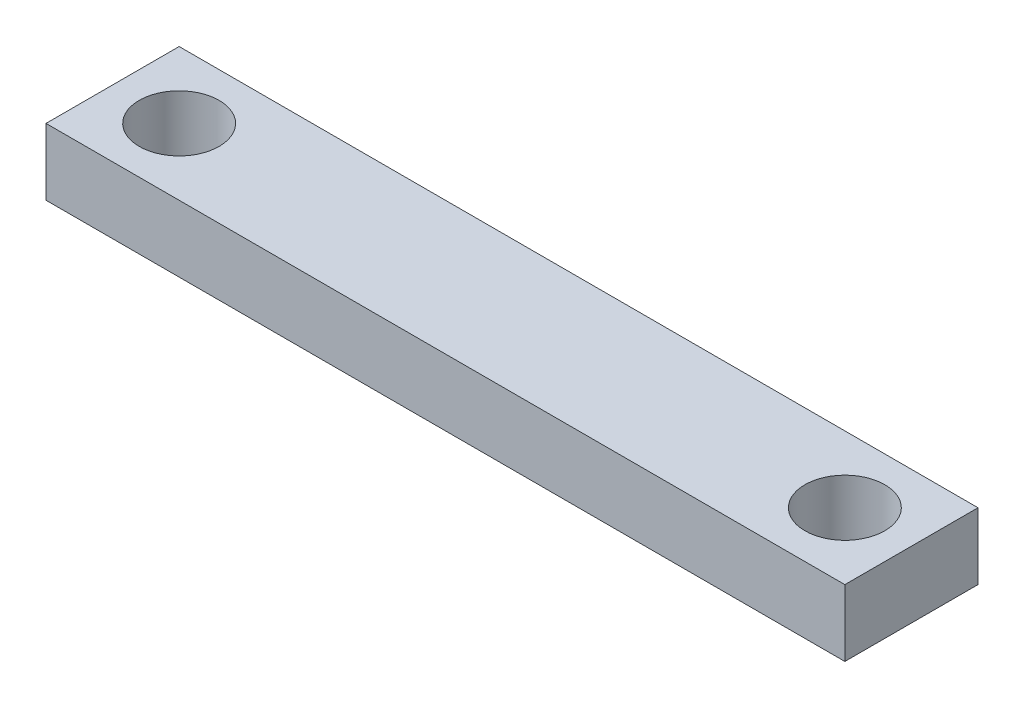
SolidWorks part; units mm, degrees
ref_plane "Front Plane" through (0, 0, 0) normal (0, 0, 1) x (1, 0, 0)
ref_plane "Top Plane" through (0, 0, 0) normal (0, 1, 0) x (1, 0, 0)
ref_plane "Right Plane" through (0, 0, 0) normal (1, 0, 0) x (0, 0, -1)
sketch "Sketch1" plane through (0, 0, 0) normal (0, 1, 0) x (1, 0, 0)
  line L1 (30, 5) -> (-30, 5)
  line L2 (30, 5) -> (30, -5)
  line L3 (30, -5) -> (-30, -5)
  line L4 (-30, 5) -> (-30, -5)
  line L5 (30, 5) -> (-30, -5) construction
  line L6 (30, -5) -> (-30, 5) construction
  circle A0 centre (-25, 0) radius 3
  circle A1 centre (25, 0) radius 3
  point P0 (0, 0)
  dimension "D3" = 6
  dimension "D1" = 10
  dimension "D2" = 60
  dimension "D4" = 5
  dimension "D5" = 5
  dimension "D6" = 50
extrude "Boss-Extrude1" add sketch "Sketch1" along normal mid plane 5
equation "\"D2@Sketch1\"= \"D6@Sketch1\" + 10mm"
